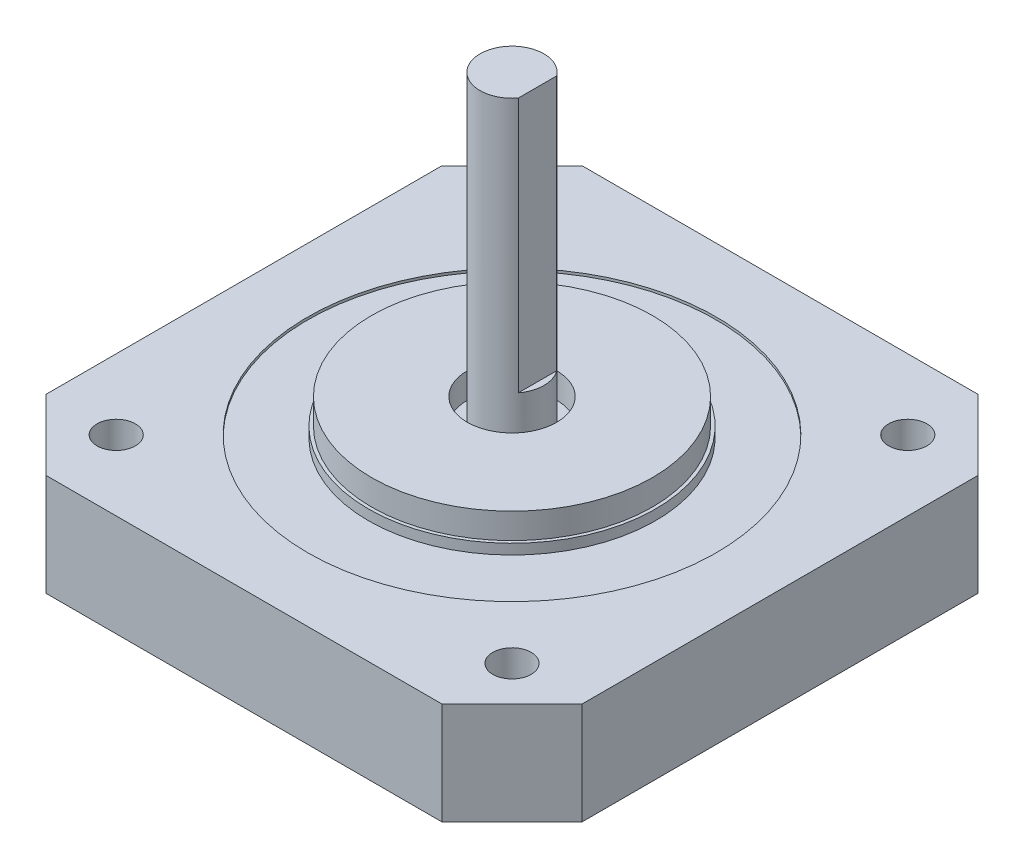
SolidWorks part; units mm, degrees
ref_plane "Front Plane" through (0, 0, 0) normal (0, 0, 1) x (1, 0, 0)
ref_plane "Top Plane" through (0, 0, 0) normal (0, 1, 0) x (1, 0, 0)
ref_plane "Right Plane" through (0, 0, 0) normal (1, 0, 0) x (0, 0, -1)
sketch "Sketch1" plane through (0, 0, 0) normal (0, 1, 0) x (1, 0, 0)
  line L1 (-21, 21) -> (21, 21)
  line L2 (-21, 21) -> (-21, -21)
  line L3 (-21, -21) -> (21, -21)
  line L4 (21, 21) -> (21, -21)
  line L5 (-21, 21) -> (21, -21) construction
  line L6 (-21, -21) -> (21, 21) construction
  point P0 (0, 0)
  dimension "D1" = 42
  dimension "D2" = 42
extrude "Nema 17" add sketch "Sketch1" along normal blind 8
chamfer "Chamfer1" distance 5.5 angle 45 4 edges at (-21, 4, -21) (21, 4, -21) (21, 4, 21) (-21, 4, 21)
sketch "Sketch2" plane through (0, 0, 0) normal (0, -1, 0) x (1, 0, 0)
  line L0 (-21, -15.5) -> (-21, 15.5) construction
  line L1 (15.5, -21) -> (-15.5, -21) construction
  line L2 (0, 0) -> (0, 21) construction
  line L4 (0, 0) -> (21, 0) construction
  circle A0 centre (-15.5, -15.5) radius 1.5
  circle A1 centre (15.5, -15.5) radius 1.5
  circle A2 centre (-15.5, 15.5) radius 1.5
  circle A3 centre (15.5, 15.5) radius 1.5
  dimension "D1" = 5.5
  dimension "D2" = 3
  dimension "D3" = 5.5
extrude "M6 Bolt Holes" cut sketch "Sketch2" against normal through all
sketch "Sketch3" plane through (0, 8, 0) normal (0, 1, 0) x (1, 0, 0)
  circle A0 centre (0, 0) radius 16
  dimension "D1" = 32
extrude "Cut-Extrude1" cut sketch "Sketch3" against normal blind 0.2
sketch "Sketch4" plane through (0, 7.8, 0) normal (0, 1, 0) x (1, 0, 0)
  circle A0 centre (0, 0) radius 11.25
  dimension "D1" = 22.5
extrude "Boss-Extrude1" add sketch "Sketch4" along normal blind 0.8
sketch "Sketch5" plane through (0, 8.6, 0) normal (0, 1, 0) x (1, 0, 0)
  circle A0 centre (0, 0) radius 11
  dimension "D1" = 22
extrude "Boss-Extrude2" add sketch "Sketch5" along normal blind 2
sketch "Sketch6" plane through (0, 8.6, 0) normal (0, 1, 0) x (1, 0, 0)
  circle A0 centre (0, 0) radius 3.5
  dimension "D1" = 7
extrude "Cut-Extrude2" cut sketch "Sketch6" along normal through all
sketch "Sketch7" plane through (0, 8.6, 0) normal (0, 1, 0) x (1, 0, 0)
  circle A0 centre (0, 0) radius 2.5
  dimension "D1" = 5
extrude "Boss-Extrude3" add sketch "Sketch7" along normal blind 24
sketch "Sketch9" plane through (0, 32.6, 0) normal (0, 1, 0) x (1, 0, 0)
  line L0 (2, 1.5) -> (2, -1.5)
  circle A0 centre (0, 0) radius 2.5 construction
  circle A1 centre (0, 0) radius 2.5 construction
  arc A2 (2, 1.5) -> (2, -1.5) centre (0, 0) cw
  dimension "D1" = 2
extrude "Cut-Extrude3" cut sketch "Sketch9" against normal blind 20
